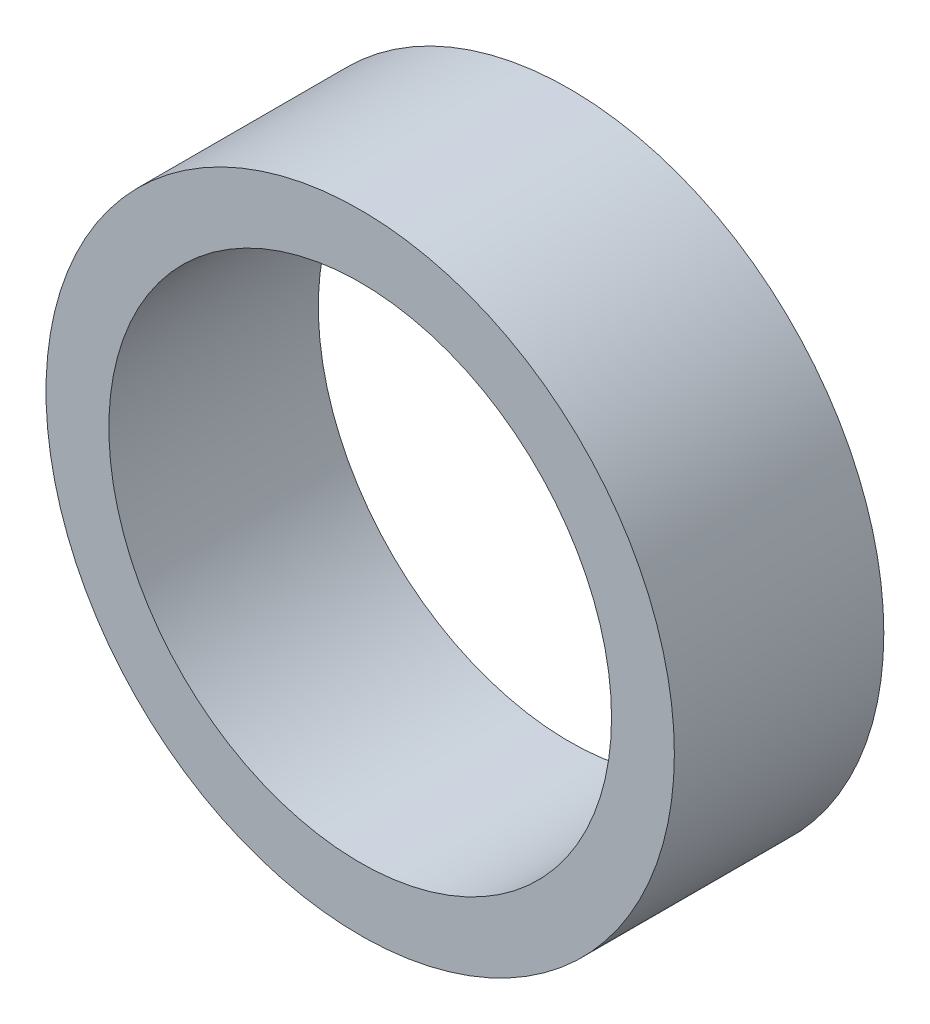
SolidWorks part; units mm, degrees
ref_plane "정면" through (0, 0, 0) normal (0, 0, 1) x (1, 0, 0)
ref_plane "윗면" through (0, 0, 0) normal (0, 1, 0) x (1, 0, 0)
ref_plane "우측면" through (0, 0, 0) normal (1, 0, 0) x (0, 0, -1)
sketch "스케치1" plane through (0, 0, 0) normal (0, 0, 1) x (1, 0, 0)
  circle A0 centre (0, 0) radius 7.5
  circle A1 centre (0, 0) radius 6
  dimension "D1" = 15
  dimension "D2" = 12
extrude "보스-돌출1" add sketch "스케치1" along normal blind 5 contours A0
